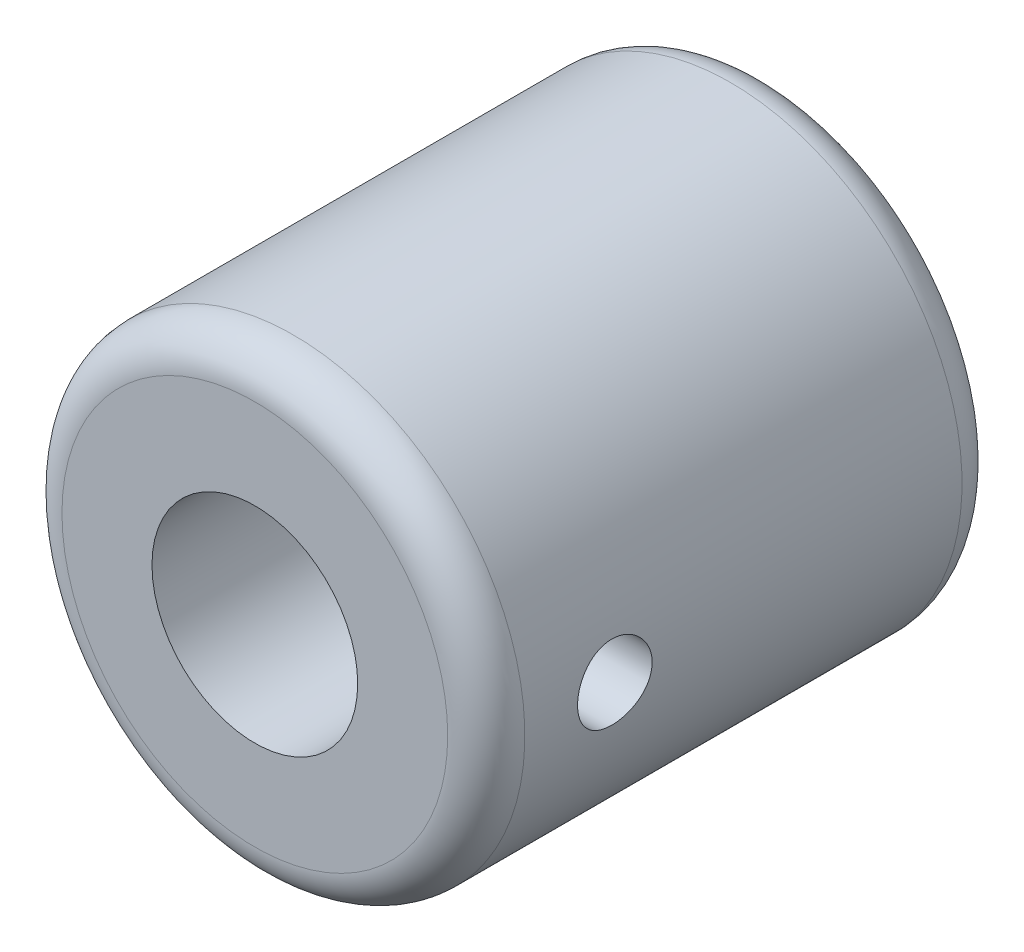
SolidWorks part; units mm, degrees
ref_plane "Front Plane" through (0, 0, 0) normal (0, 0, 1) x (1, 0, 0)
ref_plane "Top Plane" through (0, 0, 0) normal (0, 1, 0) x (1, 0, 0)
ref_plane "Right Plane" through (0, 0, 0) normal (1, 0, 0) x (0, 0, -1)
ref_plane "Plane1" through (0, 0, 0) normal (0, -1, 0) x (1, 0, 0)
sketch "Sketch1" plane through (0, 0, 0) normal (0, -1, 0) x (1, 0, 0)
  line L0 (7.5, 20) -> (0, 20)
  line L1 (0, 20) -> (0, 0)
  line L2 (0, 0) -> (7.5, 0)
  line L3 (9, 1.5) -> (9, 18.5)
  line L4 (0, 20) -> (0, 0) construction
  arc A0 (7.5, 0) -> (9, 1.5) centre (7.5, 1.5) ccw
  arc A1 (9, 18.5) -> (7.5, 20) centre (7.5, 18.5) ccw
revolve "Revolve1" add sketch "Sketch1" angle 360 about L4
hole_wizard "Ø8.0 (8) Diameter Hole1" positions "Sketch3" profile "Sketch2" hole size "Ø8.0" standard "ANSI Metric"
sketch "Sketch3" plane through (0, 0, 20) normal (0, 0, 1) x (1, 0, 0)
  point P0 (0, 0)
sketch "Sketch2" plane through (0, 0, 20) normal (1, 0, 0) x (0, -1, 0)
  line L0 (0, 0) -> (0, 10)
  line L1 (0, 10) -> (4, 10)
  line L2 (4, 10) -> (4, 0)
  line L5 (4, 0) -> (0, 0)
  line L10 (0, 10) -> (-4, 10) construction
  line L11 (0, -6.35) -> (0, 107.95) construction
  dimension "Hole Dia." = 8
  dimension "Hole Depth" = 10
  dimension "Drill Angle" = 180
ref_plane "Plane2" through (3.7279, 0, 0) normal (-1, 0, 0) x (0, 0, 1)
hole_wizard "Ø2.9 (2.9) Diameter Hole1" positions "Sketch5" profile "Sketch4" hole size "Ø2.9" standard "ANSI Metric"
sketch "Sketch5" plane through (3.7279, 0, 0) normal (-1, 0, 0) x (0, 0, 1)
  point P0 (15, 0)
sketch "Sketch4" plane through (3.7279, 0, 15) normal (0, 1, 0) x (0, 0, 1)
  line L0 (0, 0) -> (0, 18)
  line L1 (0, 18) -> (1.45, 18)
  line L2 (1.45, 18) -> (1.45, 0)
  line L5 (1.45, 0) -> (0, 0)
  line L10 (0, 18) -> (-1.45, 18) construction
  line L11 (0, -6.35) -> (0, 107.95) construction
  dimension "Hole Dia." = 2.9
  dimension "Hole Depth" = 18
  dimension "Drill Angle" = 180
